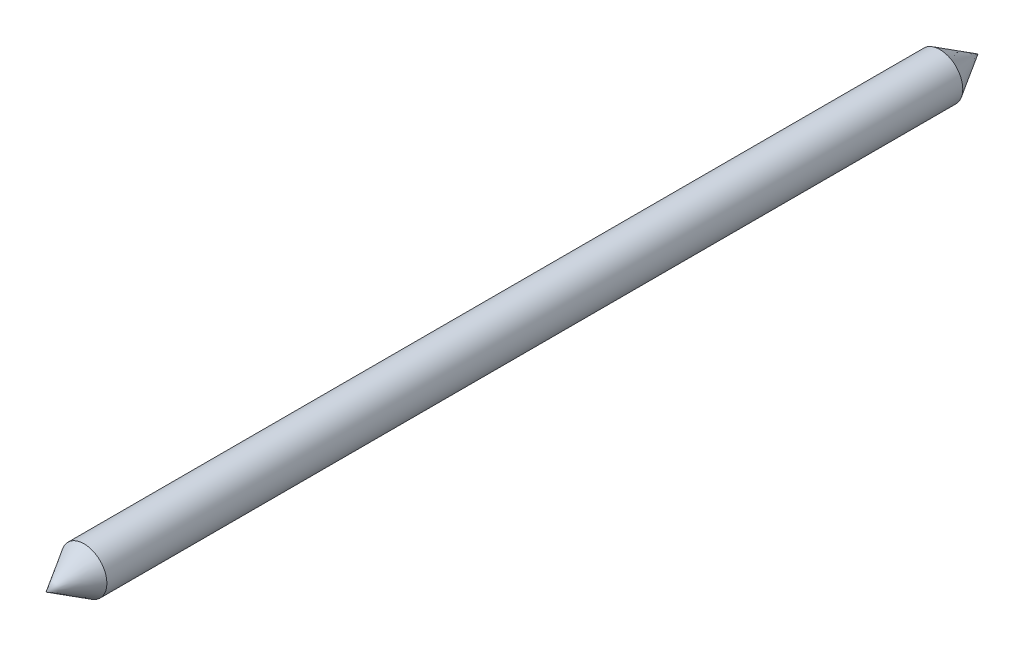
SolidWorks part; units mm, degrees
ref_plane "Front Plane" through (0, 0, 0) normal (0, 0, 1) x (1, 0, 0)
ref_plane "Top Plane" through (0, 0, 0) normal (0, 1, 0) x (1, 0, 0)
ref_plane "Right Plane" through (0, 0, 0) normal (1, 0, 0) x (0, 0, -1)
sketch "Sketch1" plane through (0, 0, 0) normal (0, 1, 0) x (1, 0, 0)
  line L0 (0, 155.575) -> (7.62, 142.875)
  line L1 (7.62, 142.875) -> (7.62, -142.875)
  line L2 (7.62, -142.875) -> (0, -155.575)
  line L3 (0, 155.575) -> (0, -155.575)
  point P7 (7.62, 0)
  dimension "D1" = 12.7
  dimension "D2" = 12.7
  dimension "D3" = 7.62
  dimension "D4" = 311.15
revolve "Revolve1" add sketch "Sketch1" angle 360 about L3
